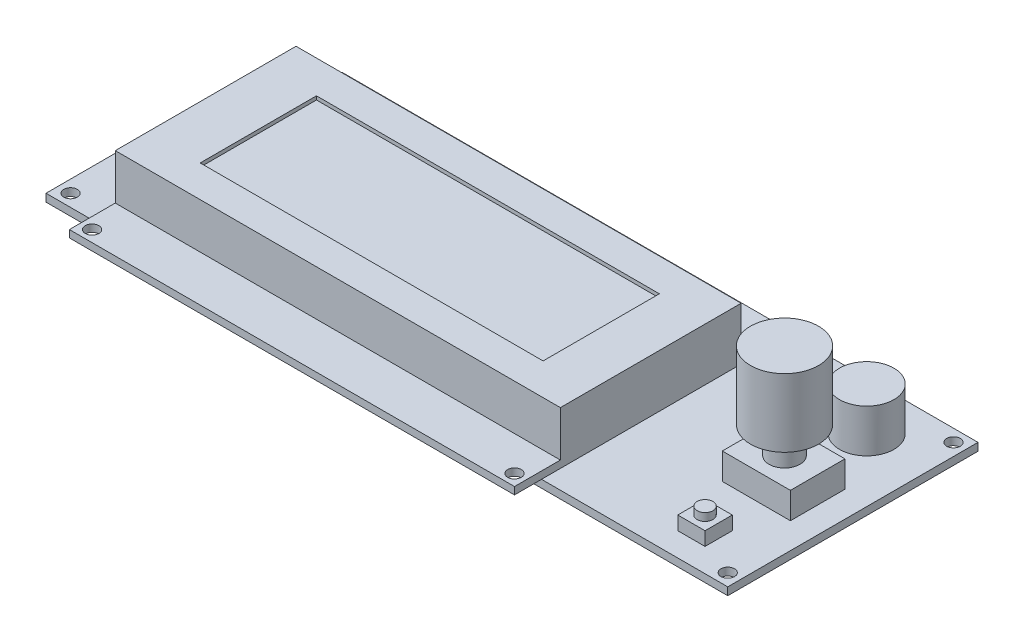
SolidWorks part; units mm, degrees
ref_plane "Front Plane" through (0, 0, 0) normal (0, 0, 1) x (1, 0, 0)
ref_plane "Top Plane" through (0, 0, 0) normal (0, 1, 0) x (1, 0, 0)
ref_plane "Right Plane" through (0, 0, 0) normal (1, 0, 0) x (0, 0, -1)
sketch "Sketch1" plane through (0, 0, 0) normal (0, 1, 0) x (1, 0, 0)
  line L1 (-75.05, -27.55) -> (75.05, -27.55)
  line L2 (-75.05, -27.55) -> (-75.05, 27.55)
  line L3 (-75.05, 27.55) -> (75.05, 27.55)
  line L4 (75.05, -27.55) -> (75.05, 27.55)
  line L5 (-75.05, -27.55) -> (75.05, 27.55) construction
  line L6 (-75.05, 27.55) -> (75.05, -27.55) construction
  circle A0 centre (-72.35, 24.85) radius 1.5
  circle A1 centre (-72.35, -24.85) radius 1.5
  circle A2 centre (72.35, 24.85) radius 1.5
  circle A3 centre (72.35, -24.85) radius 1.5
  point P0 (0, 0)
  dimension "D3" = 3
  dimension "D4" = 2.7
  dimension "D5" = 2.7
  dimension "D6" = 3
  dimension "D7" = 2.7
  dimension "D8" = 2.7
  dimension "D9" = 3
  dimension "D10" = 2.7
  dimension "D11" = 2.7
  dimension "D12" = 3
  dimension "D14" = 2.7
  dimension "D1" = 55.1
  dimension "D2" = 150.1
  dimension "D13" = 2.7
extrude "Boss-Extrude1" add sketch "Sketch1" along normal blind 1.7
sketch "Sketch2" plane through (0, 1.7, 0) normal (0, 1, 0) x (1, 0, 0)
  line L0 (-75.05, 27.55) -> (-75.05, -27.55) construction
  line L1 (-53.25, 23.15) -> (-12.45, 23.15)
  line L2 (-53.25, 23.15) -> (-53.25, 20.65)
  line L3 (-53.25, 20.65) -> (-12.45, 20.65)
  line L4 (-12.45, 23.15) -> (-12.45, 20.65)
  line L5 (75.05, 27.55) -> (-75.05, 27.55) construction
  dimension "D1" = 40.8
  dimension "D2" = 2.5
  dimension "D3" = 21.8
  dimension "D4" = 4.4
extrude "Boss-Extrude2" add sketch "Sketch2" along normal blind 2.4
sketch "Sketch3" plane through (0, 4.1, 0) normal (0, 1, 0) x (1, 0, 0)
  line L0 (75.05, 27.55) -> (-75.05, 27.55) construction
  line L1 (-61.55, 24.1) -> (36.45, 24.1)
  line L2 (-61.55, 24.1) -> (-61.55, -35.9)
  line L3 (-61.55, -35.9) -> (36.45, -35.9)
  line L4 (36.45, 24.1) -> (36.45, -35.9)
  line L5 (-75.05, 27.55) -> (-75.05, -27.55) construction
  circle A0 centre (-59.05, 21.6) radius 1.5
  circle A1 centre (33.95, 21.6) radius 1.5
  circle A2 centre (33.95, -33.4) radius 1.5
  circle A3 centre (-59.05, -33.4) radius 1.5
  dimension "D5" = 3
  dimension "D6" = 2.5
  dimension "D7" = 2.5
  dimension "D8" = 2.5
  dimension "D9" = 2.5
  dimension "D1" = 60
  dimension "D2" = 98
  dimension "D3" = 3.45
  dimension "D4" = 13.5
extrude "Boss-Extrude3" add sketch "Sketch3" along normal blind 1.6
sketch "Sketch4" plane through (0, 5.7, 0) normal (0, 1, 0) x (1, 0, 0)
  line L0 (-61.55, 24.1) -> (-61.55, -35.9) construction
  line L1 (-61.55, 14) -> (36.45, 14)
  line L2 (-61.55, 14) -> (-61.55, -25.8)
  line L3 (-61.55, -25.8) -> (36.45, -25.8)
  line L4 (36.45, 14) -> (36.45, -25.8)
  line L5 (36.45, -35.9) -> (36.45, 24.1) construction
  line L6 (-61.55, -35.9) -> (36.45, -35.9) construction
  dimension "D1" = 39.8
  dimension "D2" = 10.1
extrude "Boss-Extrude4" add sketch "Sketch4" along normal blind 10
sketch "Sketch5" plane through (0, 15.7, 0) normal (0, 1, 0) x (1, 0, 0)
  line L0 (-61.55, -25.8) -> (36.45, -25.8) construction
  line L1 (-49.85, 6.8) -> (25.65, 6.8)
  line L2 (-49.85, 6.8) -> (-49.85, -18.8)
  line L3 (-49.85, -18.8) -> (25.65, -18.8)
  line L4 (25.65, 6.8) -> (25.65, -18.8)
  line L5 (36.45, -25.8) -> (36.45, 14) construction
  dimension "D1" = 7
  dimension "D2" = 10.8
  dimension "D3" = 25.6
  dimension "D4" = 75.5
extrude "Cut-Extrude1" cut sketch "Sketch5" against normal blind 0.8
sketch "Sketch6" plane through (0, 1.7, 0) normal (0, 1, 0) x (1, 0, 0)
  line L0 (75.05, 27.55) -> (-75.05, 27.55) construction
  line L1 (75.05, -27.55) -> (75.05, 27.55) construction
  circle A0 centre (61.15, 16.95) radius 6
  dimension "D1" = 12
  dimension "D2" = 10.6
  dimension "D3" = 13.9
extrude "Boss-Extrude5" add sketch "Sketch6" along normal blind 9.5
sketch "Sketch7" plane through (0, 1.7, 0) normal (0, 1, 0) x (1, 0, 0)
  line L0 (-75.05, -27.55) -> (75.05, -27.55) construction
  line L1 (58.85, -16.35) -> (64.85, -16.35)
  line L2 (58.85, -16.35) -> (58.85, -22.35)
  line L3 (58.85, -22.35) -> (64.85, -22.35)
  line L4 (64.85, -16.35) -> (64.85, -22.35)
  line L5 (75.05, -27.55) -> (75.05, 27.55) construction
  dimension "D1" = 6
  dimension "D2" = 6
  dimension "D3" = 5.2
  dimension "D4" = 10.2
extrude "Boss-Extrude6" add sketch "Sketch7" along normal blind 3
sketch "Sketch8" plane through (0, 4.7, 0) normal (0, 1, 0) x (1, 0, 0)
  line L1 (64.85, -22.35) -> (64.85, -16.35) construction
  line L2 (58.85, -22.35) -> (64.85, -22.35) construction
  circle A0 centre (61.85, -19.35) radius 1.75
  point P8 (64.85, -19.35)
  point P9 (61.85, -22.35)
  dimension "D1" = 3.5
extrude "Boss-Extrude7" add sketch "Sketch8" along normal blind 1.7
sketch "Sketch9" plane through (0, 0, 0) normal (0, -1, 0) x (1, 0, 0)
  line L0 (-75.05, -27.55) -> (-75.05, 27.55) construction
  line L1 (-75.05, -7.25) -> (-48.75, -7.25)
  line L2 (-75.05, -7.25) -> (-75.05, 19.25)
  line L3 (-75.05, 19.25) -> (-48.75, 19.25)
  line L4 (-48.75, -7.25) -> (-48.75, 19.25)
  line L5 (-75.05, 27.55) -> (75.05, 27.55) construction
  dimension "D1" = 26.5
  dimension "D2" = 26.3
  dimension "D3" = 8.3
extrude "Boss-Extrude8" add sketch "Sketch9" along normal blind 2.8
sketch "Sketch10" plane through (0, 0, 0) normal (0, -1, 0) x (1, 0, 0)
  line L0 (75.05, 27.55) -> (75.05, -27.55) construction
  line L1 (14.05, -5.65) -> (-6.15, -5.65)
  line L2 (14.05, -5.65) -> (14.05, 2.95)
  line L3 (14.05, 2.95) -> (-6.15, 2.95)
  line L4 (-6.15, -5.65) -> (-6.15, 2.95)
  line L5 (-8.95, -5.65) -> (-29.15, -5.65)
  line L6 (-8.95, -5.65) -> (-8.95, 2.95)
  line L7 (-8.95, 2.95) -> (-29.15, 2.95)
  line L8 (-29.15, -5.65) -> (-29.15, 2.95)
  line L9 (75.05, -27.55) -> (-75.05, -27.55) construction
  dimension "D1" = 20.2
  dimension "D2" = 20.2
  dimension "D3" = 8.6
  dimension "D4" = 61
  dimension "D5" = 43.2
  dimension "D6" = 21.9
extrude "Boss-Extrude9" add sketch "Sketch10" along normal blind 9
sketch "Sketch11" plane through (0, 0, 0) normal (0, -1, 0) x (1, 0, 0)
  line L0 (-75.05, -27.55) -> (-75.05, -7.25) construction
  line L1 (75.05, -27.55) -> (-75.05, -27.55) construction
  circle A0 centre (-62, -16.5) radius 4.65
  dimension "D1" = 9.3
  dimension "D2" = 13.05
  dimension "D3" = 11.05
extrude "Boss-Extrude10" add sketch "Sketch11" along normal blind 9
sketch "Sketch12" plane through (0, 1.7, 0) normal (0, 1, 0) x (1, 0, 0)
  line L0 (75.05, -27.55) -> (75.05, 27.55) construction
  line L1 (69.35, 3.95) -> (54.35, 3.95)
  line L2 (69.35, 3.95) -> (69.35, -8.05)
  line L3 (69.35, -8.05) -> (54.35, -8.05)
  line L4 (54.35, 3.95) -> (54.35, -8.05)
  line L5 (75.05, 27.55) -> (-75.05, 27.55) construction
  dimension "D1" = 15
  dimension "D2" = 12
  dimension "D3" = 5.7
  dimension "D4" = 23.6
extrude "Boss-Extrude11" add sketch "Sketch12" along normal blind 5.8
sketch "Sketch13" plane through (0, 7.5, 0) normal (0, 1, 0) x (1, 0, 0)
  line L1 (54.35, 3.95) -> (54.35, -8.05) construction
  line L2 (69.35, -8.05) -> (69.35, 3.95) construction
  circle A0 centre (62.05, -2.05) radius 3.4
  point P8 (54.35, -2.05)
  dimension "D1" = 6.8
  dimension "D2" = 7.3
extrude "Boss-Extrude12" add sketch "Sketch13" along normal blind 5.9
sketch "Sketch14" plane through (0, 13.4, 0) normal (0, 1, 0) x (1, 0, 0)
  circle A0 centre (62.05, -2.05) radius 7.5
  dimension "D1" = 15
extrude "Boss-Extrude13" add sketch "Sketch14" along normal blind 15
